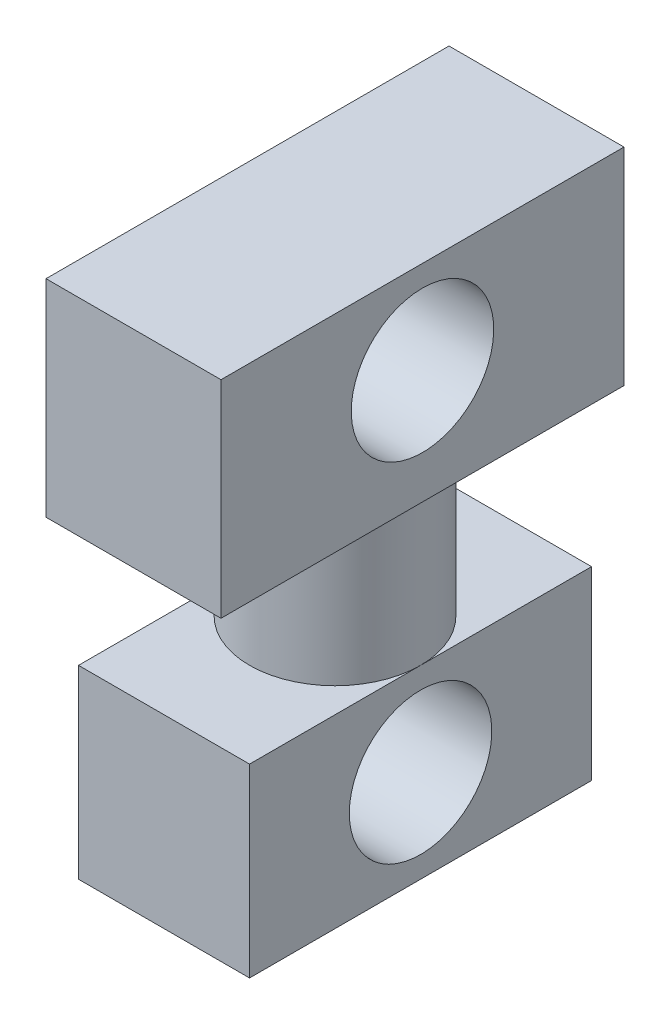
SolidWorks part; units mm, degrees
ref_plane "Front Plane" through (0, 0, 0) normal (0, 0, 1) x (1, 0, 0)
ref_plane "Top Plane" through (0, 0, 0) normal (0, 1, 0) x (1, 0, 0)
ref_plane "Right Plane" through (0, 0, 0) normal (1, 0, 0) x (0, 0, -1)
sketch "Sketch1" plane through (0, 0, 0) normal (0, 0, 1) x (1, 0, 0)
  line L0 (0, 35.2363) -> (12.28, 35.2363)
  line L1 (12.28, 35.2363) -> (12.28, 20.7363)
  line L2 (12.28, 20.7363) -> (0, 20.7363)
  line L3 (0, 20.7363) -> (0, 35.2363)
extrude "Boss-Extrude1" add sketch "Sketch1" along normal blind 28.28
sketch "Sketch2" plane through (12.28, 0, 0) normal (1, 0, 0) x (0, 0, -1)
  line L2 (-14.14, 35.2363) -> (-14.14, 28.7363)
  line L3 (-28.28, 35.2363) -> (0, 35.2363) construction
  circle A0 centre (-14.14, 28.7363) radius 5
extrude "Cut-Extrude1" cut sketch "Sketch2" against normal blind 28.27
sketch "Sketch3" plane through (0, 20.7363, 0) normal (0, -1, 0) x (1, 0, 0)
  line L0 (0, 14.14) -> (6.14, 14.14)
  line L1 (0, 28.28) -> (0, 0) construction
  circle A0 centre (6.14, 14.14) radius 6
extrude "Boss-Extrude2" add sketch "Sketch3" along normal blind 10
sketch "Sketch4" plane through (0, 10.7363, 0) normal (0, -1, 0) x (1, 0, 0)
  line L0 (0.14, 14.14) -> (0.14, 2.14)
  line L1 (0.14, 2.14) -> (12.1432, 2.14)
  line L2 (12.1432, 2.14) -> (12.1432, 26.14)
  line L3 (12.1432, 26.14) -> (2.0912, 26.14)
  line L4 (2.0912, 26.14) -> (4.0902, 26.14)
  line L5 (0.14, 14.14) -> (0.14, 26.14)
  line L6 (0.14, 26.14) -> (2.0912, 26.14)
  circle A0 centre (6.14, 14.14) radius 6 construction
  circle M5 centre (6.14, 14.14) radius 6
extrude "Boss-Extrude3" add sketch "Sketch4" along normal blind 13 contours L6 L5 L0 L1 L2 L3 M5 | M5
sketch "Sketch5" plane through (0.14, 0, 0) normal (-1, 0, 0) x (0, 0, 1)
  line L0 (14.14, 10.7363) -> (14.14, 4.2363)
  circle A0 centre (14.14, 4.2363) radius 5
extrude "Cut-Extrude2" cut sketch "Sketch5" against normal blind 13
